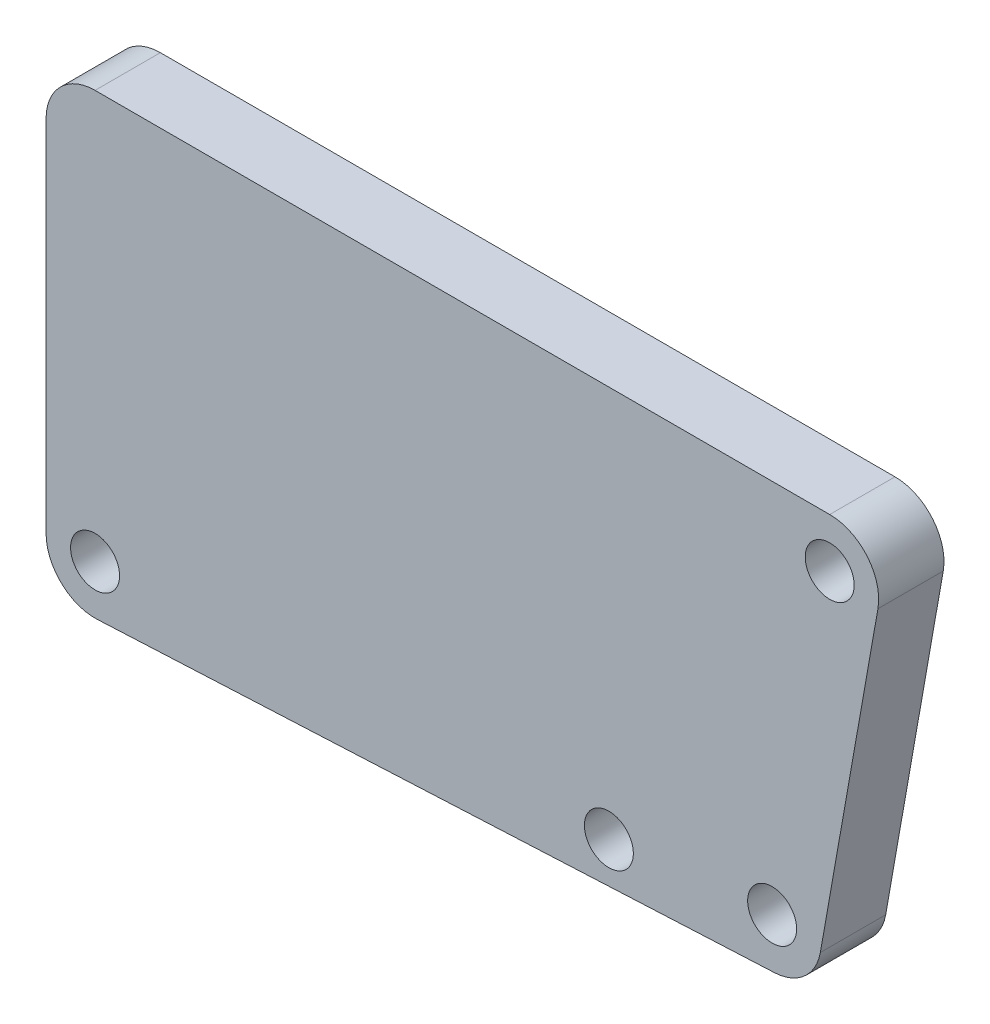
SolidWorks part; units mm, degrees
ref_plane "Front Plane" through (0, 0, 0) normal (0, 0, 1) x (1, 0, 0)
ref_plane "Top Plane" through (0, 0, 0) normal (0, 1, 0) x (1, 0, 0)
ref_plane "Right Plane" through (0, 0, 0) normal (1, 0, 0) x (0, 0, -1)
sketch "Sketch1" plane through (0, 0, 0) normal (0, 0, 1) x (1, 0, 0)
  line L0 (0, 3) -> (45, 3)
  line L1 (47.9544, -0.5209) -> (44.4279, -20.5209)
  line L2 (41.618, -22.9965) -> (0.1445, -24.9965)
  line L3 (-3, -22) -> (-3, 0)
  circle A0 centre (45, 0) radius 1.5
  circle A1 centre (41.4735, -20) radius 1.5
  circle A2 centre (31.4735, -21) radius 1.5
  arc A3 (45, 3) -> (47.9544, -0.5209) centre (45, 0) cw
  arc A4 (44.4279, -20.5209) -> (41.618, -22.9965) centre (41.4735, -20) cw
  arc A5 (-3, -22) -> (0.1445, -24.9965) centre (0, -22) ccw
  circle A6 centre (0, -22) radius 1.5
  arc A7 (-3, 0) -> (0, 3) centre (0, 0) cw
  point P0 (48.1978, -0.5209)
  point P19 (1.1631, -0.1332)
  point P20 (0, 0)
  dimension "D1" = 3
  dimension "D6" = 3
  dimension "D9" = 3
  dimension "D2" = 3
  dimension "D3" = 20
  dimension "D4" = 80
  dimension "D5" = 3
  dimension "D7" = 1
  dimension "D8" = 10
  dimension "D10" = 25
  dimension "D11" = 45
extrude "Boss-Extrude1" add sketch "Sketch1" along normal blind 4
